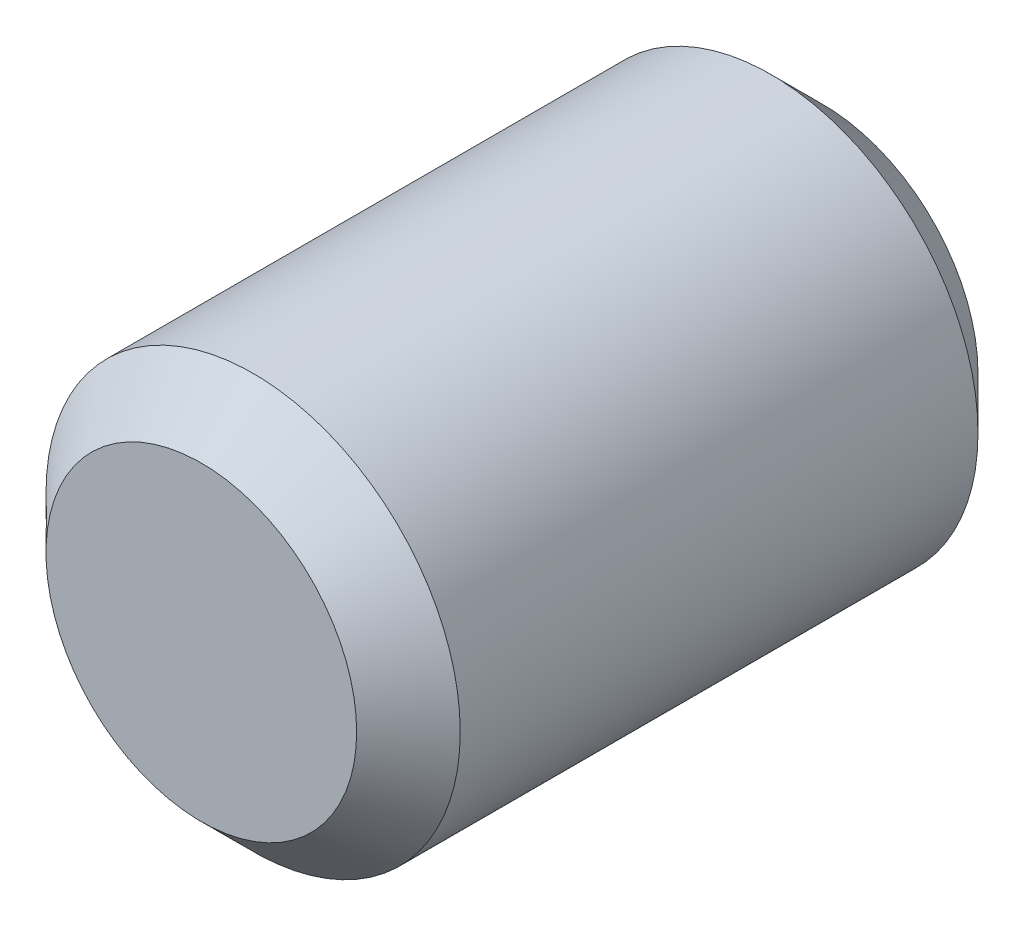
SolidWorks part; units mm, degrees
ref_plane "Ebene vorne" through (0, 0, 0) normal (0, 0, 1) x (1, 0, 0)
ref_plane "Ebene oben" through (0, 0, 0) normal (0, 1, 0) x (1, 0, 0)
ref_plane "Ebene rechts" through (0, 0, 0) normal (1, 0, 0) x (0, 0, -1)
sketch "Sketch1" plane through (0, 0, 0) normal (0, 0, 1) x (1, 0, 0)
  circle A0 centre (0, 0) radius 2
  dimension "D1" = 4
extrude "Boss-Extrude1" add sketch "Sketch1" along normal blind 6
chamfer "Chamfer2" distance 0.5 angle 45 2 edges at (2, 0, 0) (2, 0, 6)
